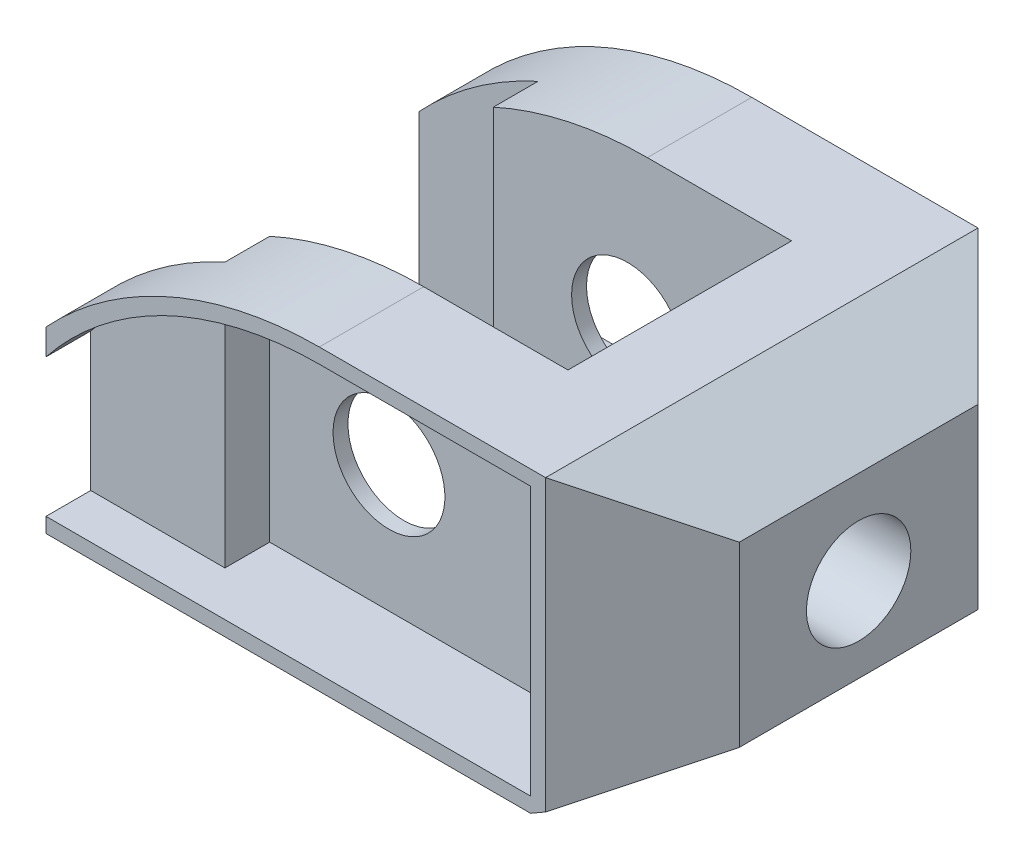
SolidWorks part; units mm, degrees
material "1060 Alloy"
ref_plane "Front Plane" through (0, 0, 0) normal (0, 0, 1) x (1, 0, 0)
ref_plane "Top Plane" through (0, 0, 0) normal (0, 1, 0) x (1, 0, 0)
ref_plane "Right Plane" through (0, 0, 0) normal (1, 0, 0) x (0, 0, -1)
sketch "Sketch2" plane through (0, 0, 0) normal (0, 0, 1) x (1, 0, 0)
  line L0 (-21.8446, 0) -> (21.8446, 0) construction
  line L1 (0, -21.0556) -> (0, 21.0556) construction
  line L2 (-34, 5) -> (-34, -19)
  line L3 (-34, -19) -> (31, -19)
  line L4 (31, -19) -> (46, -10.3397)
  line L5 (46, -10.3397) -> (46, 13.5)
  line L6 (46, 13.5) -> (33.0096, 21)
  line L7 (33.0096, 21) -> (2.6606, 21)
  circle A0 centre (0, 0) radius 7.5
  arc A1 (-34, 5) -> (2.6606, 21) centre (2.6606, -29) cw
  point P6 (0, 0)
  point P9 (0, 0)
  dimension "D1" = 15
  dimension "D11" = 50
  dimension "D2" = 65
  dimension "D3" = 19
  dimension "D4" = 24
  dimension "D5" = 31
  dimension "D6" = 15
  dimension "D7" = 15
  dimension "D8" = 30
  dimension "D9" = 30
  dimension "D10" = 40
extrude "Boss-Extrude1" add sketch "Sketch2" along normal blind 58
sketch "Sketch3" plane through (0, 21, 0) normal (0, 1, 0) x (1, 0, 0)
  line L0 (46, -29) -> (-34, -29) construction
  line L1 (46, -58) -> (46, 0) construction
  line L2 (-34, -58) -> (-34, 0) construction
  line L3 (2.6606, -58) -> (2.6606, 0) construction
  line L4 (22.0096, -44) -> (-18, -44)
  line L5 (22.0096, -44) -> (22.0096, -14)
  line L6 (22.0096, -14) -> (-18, -14)
  line L7 (-18, -44) -> (-18, -14)
  line L8 (33.0096, -58) -> (33.0096, 0) construction
  line L9 (33.0096, 0) -> (2.6606, 0) construction
  line L10 (33.0096, -58) -> (2.6606, -58) construction
  point P6 (2.6606, -29)
  dimension "D1" = 11
  dimension "D2" = 14
  dimension "D3" = 14
  dimension "D4" = 16
extrude "Cut-Extrude1" cut sketch "Sketch3" against normal blind 53
sketch "Sketch4" plane through (0, 21, 0) normal (0, 1, 0) x (1, 0, 0)
  line L0 (-34, -58) -> (-34, 0) construction
  line L1 (-18, -14) -> (-34, -14)
  line L2 (-18, -14) -> (-18, -8)
  line L3 (-18, -8) -> (-34, -8)
  line L4 (-34, -14) -> (-34, -8)
  line L5 (-18, -29) -> (-34, -29) construction
  line L6 (-18, -44) -> (-18, -14) construction
  line L7 (-18, -50) -> (-34, -50)
  line L8 (-34, -44) -> (-34, -50)
  line L9 (-18, -44) -> (-34, -44)
  line L10 (-18, -44) -> (-18, -50)
  dimension "D1" = 6
  dimension "D2" = 8
extrude "Cut-Extrude2" cut sketch "Sketch4" against normal blind 53
sketch "Sketch5" plane through (0, 21, 0) normal (0, 1, 0) x (1, 0, 0)
  line L0 (33.0096, 0) -> (46, -12.9904)
  line L1 (46, -58) -> (46, 0) construction
  line L2 (46, -12.9904) -> (46, 0)
  line L3 (46, 0) -> (33.0096, 0)
  line L4 (33.0096, -29) -> (46, -29) construction
  line L5 (33.0096, -58) -> (33.0096, 0) construction
  line L6 (46, -45.0096) -> (46, -58)
  line L7 (33.0096, -58) -> (46, -45.0096)
  line L8 (46, -58) -> (33.0096, -58)
  dimension "D1" = 45
extrude "Cut-Extrude3" cut sketch "Sketch5" against normal blind 53
sketch "Sketch6" plane through (46, 0, 0) normal (1, 0, 0) x (0, 0, -1)
  line L0 (-58, -19) -> (0, -19) construction
  line L1 (-58, -17.8397) -> (-58, 21) construction
  circle A0 centre (-29, 1) radius 7
  dimension "D1" = 14
  dimension "D2" = 20
  dimension "D3" = 29
extrude "Cut-Extrude4" cut sketch "Sketch6" against normal blind 53
sketch "Sketch7" plane through (0, 0, 58) normal (0, 0, 1) x (1, 0, 0)
  line L10 (-16, 15.2242) -> (-16, -17)
  line L11 (-34, 5) -> (-34, -19) construction
  line L15 (30.4641, -17) -> (31.0096, -16.685)
  line L16 (31.0096, -16.685) -> (31.0096, 19)
  line L17 (31.0096, 19) -> (2.6606, 19)
  line L18 (-32, 4.2061) -> (-32, -17)
  line L19 (-32, -17) -> (30.4641, -17)
  line L21 (31.0096, -17) -> (31.0096, 19)
  line L22 (31.0096, 19) -> (2.6606, 19)
  line L24 (-16, -17) -> (31.0096, -17)
  arc A3 (2.6606, 19) -> (-32, 4.2061) centre (2.6606, -29) ccw
  arc A4 (2.6606, 19) -> (-16, 15.2242) centre (2.6606, -29) ccw
  point P4 (0, 0)
  point P5 (0, 0)
  dimension "D2" = 18
  dimension "D1" = 2
extrude "Cut-Extrude5" cut sketch "Sketch7" against normal blind 12
sketch "Sketch8" plane through (0, 0, 58) normal (0, 0, 1) x (1, 0, 0)
  line L0 (-16, 15.2242) -> (-16, -17)
  line L1 (-16, -17) -> (-34, -17)
  line L2 (-34, 5) -> (-34, -19) construction
  line L3 (-34, -17) -> (-34, 1.5248)
  arc A0 (-34, 1.5248) -> (-16, 15.2242) centre (2.0065, -27.11) cw
  arc A1 (2.6606, 21) -> (-34, 5) centre (2.6606, -29) ccw construction
  dimension "D1" = 2
  dimension "D2" = 2
  dimension "D3" = 10.11
extrude "Cut-Extrude6" cut sketch "Sketch8" against normal blind 6
sketch "Sketch9" plane through (0, 0, 0) normal (0, 0, -1) x (-1, 0, 0)
  line L5 (16, 15.2242) -> (16, -17)
  line L6 (34, 5) -> (34, -19) construction
  line L10 (-31.0096, 19) -> (-31.0096, -16.685)
  line L11 (-31.0096, -16.685) -> (-30.4641, -17)
  line L12 (-30.4641, -17) -> (32, -17)
  line L13 (32, -17) -> (32, 4.2061)
  line L14 (-2.6606, 19) -> (-31.0096, 19)
  line L15 (-31.0096, 19) -> (-31.0096, -17)
  line L17 (-31.0096, -17) -> (16, -17)
  line L19 (-2.6606, 19) -> (-31.0096, 19)
  arc A2 (32, 4.2061) -> (-2.6606, 19) centre (-2.6606, -29) ccw
  arc A3 (16, 15.2242) -> (-2.6606, 19) centre (-2.6606, -29) ccw
  point P4 (0, 0)
  point P5 (0, 0)
  point P7 (0, 0)
  dimension "D2" = 18
  dimension "D1" = 2
extrude "Cut-Extrude7" cut sketch "Sketch9" against normal blind 12
sketch "Sketch10" plane through (0, 0, 0) normal (0, 0, -1) x (-1, 0, 0)
  line L0 (16, 15.2242) -> (16, -17)
  line L1 (16, -17) -> (34, -17)
  line L2 (34, 5) -> (34, -19) construction
  line L3 (34, -17) -> (34, 1.5248)
  arc A0 (34, 1.5248) -> (16, 15.2242) centre (-2.0065, -27.11) ccw
  arc A1 (34, 5) -> (-2.6606, 21) centre (-2.6606, -29) ccw construction
  dimension "D1" = 2
  dimension "D2" = 10.11
extrude "Cut-Extrude8" cut sketch "Sketch10" against normal blind 6
equation "\"A\"= 58mm"
equation "\"B\"= 40mm"
equation "\"C\"= 65mm"
equation "\"D2@Sketch6\"=\"B\"/2"
equation "\"D3@Sketch6\"=\"A\"/2"
